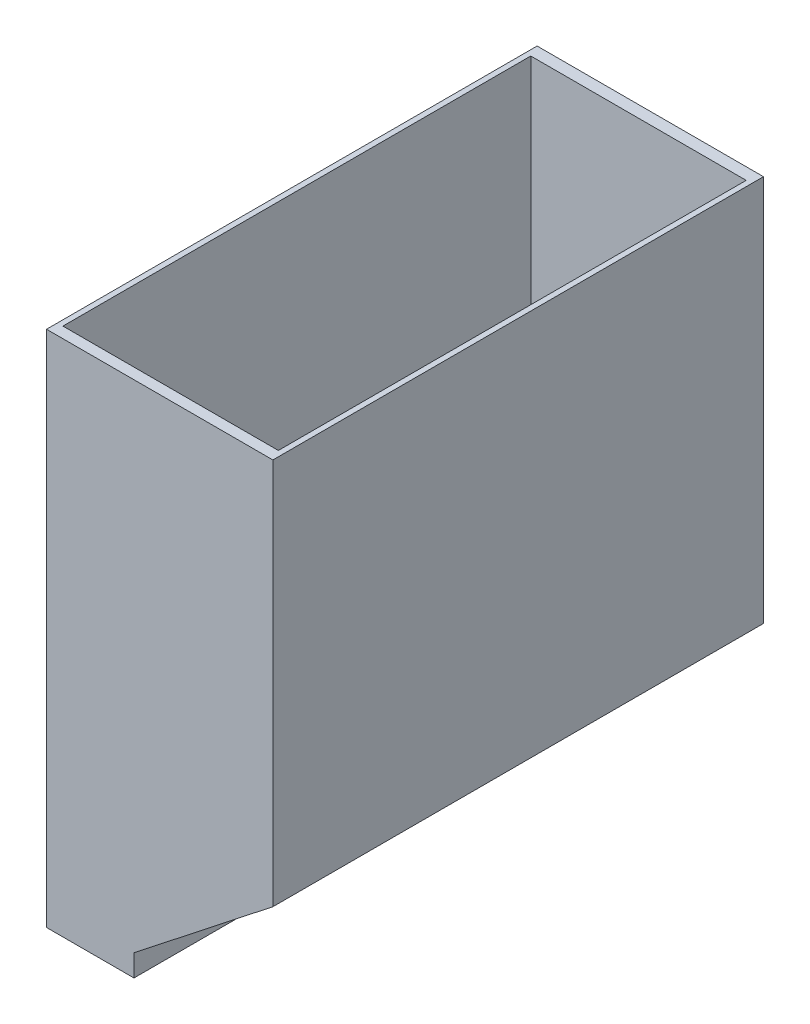
SolidWorks part; units mm, degrees
other "Marquage1"
sketch "Esquisse3" plane through (127, 224.79, 233.68) normal (0.5774, 0.5773, 0.5774) x (0.7071, 0, -0.7071)
ref_plane "Plan de face" through (0, 0, 0) normal (0, 0, 1) x (1, 0, 0)
ref_plane "Plan de dessus" through (0, 0, 0) normal (0, 1, 0) x (1, 0, 0)
ref_plane "Plan de droite" through (0, 0, 0) normal (1, 0, 0) x (0, 0, -1)
sketch "Esquisse1" plane through (0, 0, 0) normal (0, 0, 1) x (1, 0, 0)
  line L0 (-29.9, -288.29) -> (131.5, -161.29)
  line L5 (-131.5, 288.29) -> (131.5, 288.29)
  line L6 (-131.5, 288.29) -> (-131.5, -288.29)
  line L8 (131.5, 288.29) -> (131.5, -161.29)
  line L9 (-131.5, -288.29) -> (-36.25, -288.29)
  line L10 (-36.25, -288.29) -> (-36.25, -313.69)
  line L11 (-36.25, -313.69) -> (-29.9, -313.69)
  line L12 (-29.9, -288.29) -> (-29.9, -313.69)
  point P0 (-131.5, 0)
  point P5 (0, 288.29)
  dimension "D1" = 6.35
  dimension "D2" = 101.6
  dimension "D3" = 449.58
  dimension "D4" = 25.4
  dimension "D5" = 576.58
  dimension "D6" = 263
extrude "Boss.-Extru.1" add sketch "Esquisse1" along normal mid plane 570
ref_plane "Plan1" through (0, 0, 272.3) normal (0, 0, 1) x (1, 0, 0)
sketch "Esquisse2" plane through (0, 0, 272.3) normal (0, 0, 1) x (1, 0, 0)
  line L0 (-125.15, 288.29) -> (-125.15, -288.29)
  line L1 (-125.15, -288.29) -> (-40.1688, -288.29)
  line L2 (-40.1688, -288.29) -> (125.15, -158.2065)
  line L3 (125.15, -158.2065) -> (125.15, 288.29)
  line L4 (125.15, 288.29) -> (-125.15, 288.29)
  line L5 (-131.5, 288.29) -> (-131.5, -288.29) construction
  line L6 (131.5, -161.29) -> (131.5, 288.29) construction
  line L7 (-29.9, -288.29) -> (131.5, -161.29) construction
  line L8 (-131.5, -288.29) -> (-36.25, -288.29) construction
  line L9 (131.5, 288.29) -> (-131.5, 288.29) construction
  dimension "D1" = 6.35
  dimension "D2" = 6.35
  dimension "D3" = 6.35
extrude "Enlèv. mat.-Extru.1" cut sketch "Esquisse2" against normal blind 543.56
sketch "Esquisse4" plane through (-36.25, 0, 0) normal (-1, 0, 0) x (0, 0, 1)
  line L0 (285, -313.69) -> (-285, -313.69) construction
  line L1 (-285, -288.29) -> (-278.65, -288.29)
  line L2 (-285, -288.29) -> (-285, -313.69)
  line L3 (-285, -313.69) -> (-278.65, -313.69)
  line L5 (-278.65, -313.69) -> (-278.65, -288.29)
  dimension "D1" = 6.35
extrude "Boss.-Extru.2" add sketch "Esquisse4" along normal blind 95.25
mirror "Symétrie1" about plane through (0, 0, 0) normal (0, 0, 1) of "Boss.-Extru.2"
